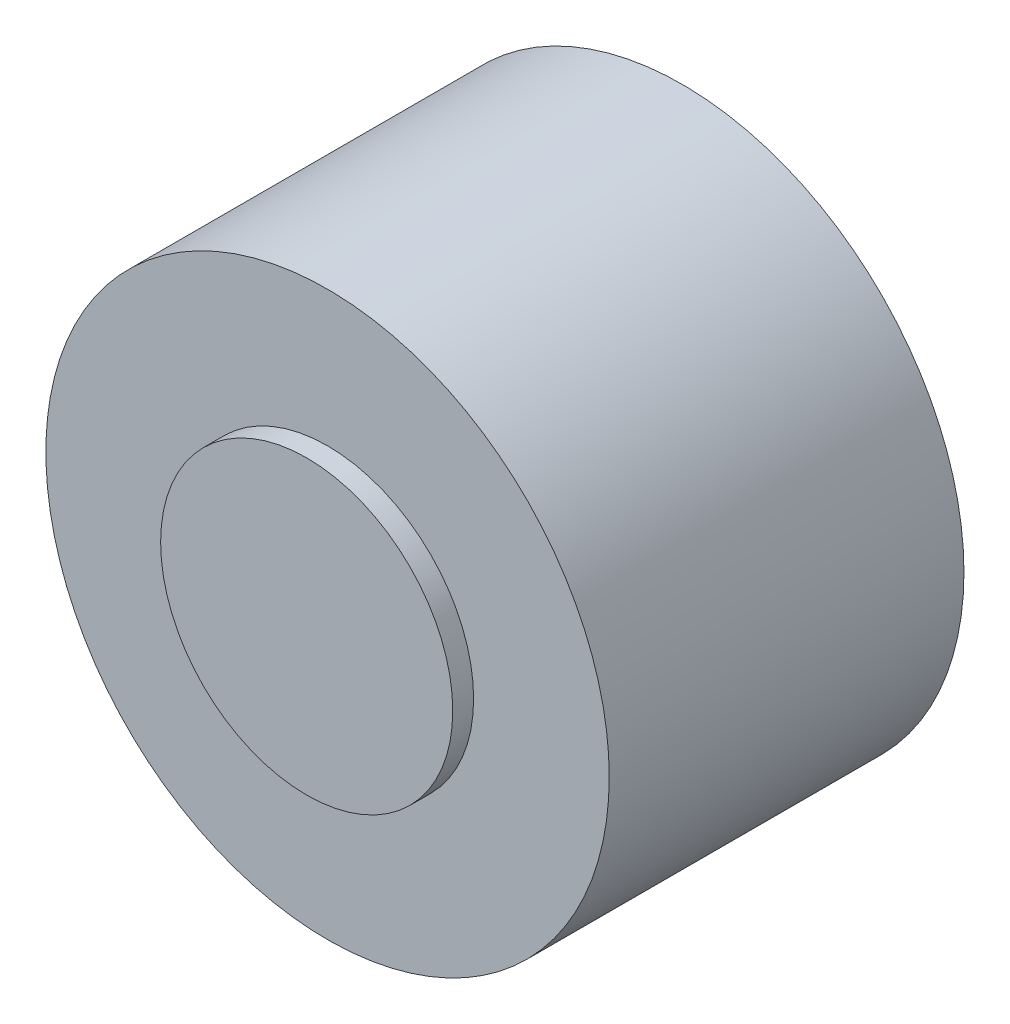
SolidWorks part; units mm, degrees
ref_plane "Спереди" through (0, 0, 0) normal (0, 0, 1) x (1, 0, 0)
ref_plane "Сверху" through (0, 0, 0) normal (0, 1, 0) x (1, 0, 0)
ref_plane "Справа" through (0, 0, 0) normal (1, 0, 0) x (0, 0, -1)
sketch "Эскиз1" plane through (0, 0, 0) normal (0, 0, 1) x (1, 0, 0)
  circle A0 centre (0, 0) radius 13.5
  dimension "D1" = 27
extrude "Бобышка-Вытянуть1" add sketch "Эскиз1" along normal blind 17
sketch "Эскиз2" plane through (0, 0, 17) normal (0, 0, 1) x (1, 0, 0)
  circle A0 centre (0, 0) radius 7
  dimension "D1" = 14
extrude "Бобышка-Вытянуть2" add sketch "Эскиз2" along normal blind 1
